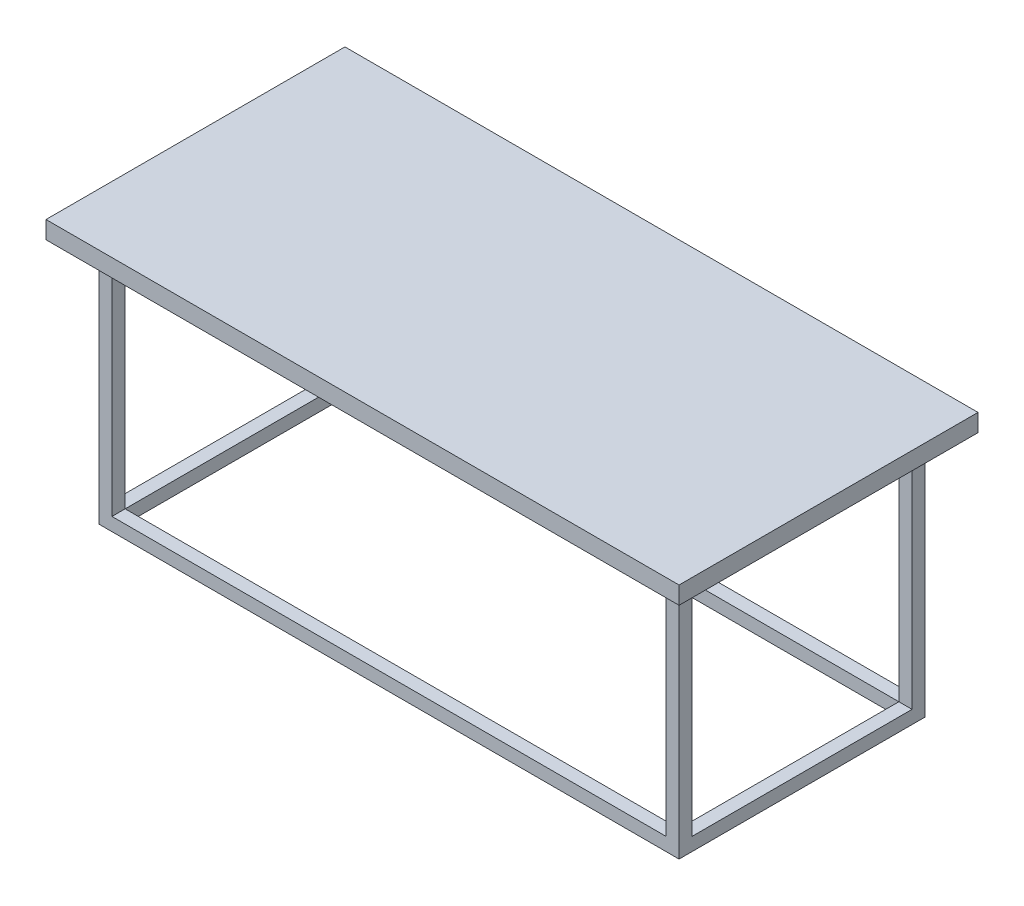
SolidWorks part; units mm, degrees
ref_plane "Front Plane" through (0, 0, 0) normal (0, 0, 1) x (1, 0, 0)
ref_plane "Top Plane" through (0, 0, 0) normal (0, 1, 0) x (1, 0, 0)
ref_plane "Right Plane" through (0, 0, 0) normal (1, 0, 0) x (0, 0, -1)
sketch "Sketch1" plane through (0, 0, 0) normal (0, 1, 0) x (1, 0, 0)
  line L1 (914.4, -431.8) -> (-914.4, -431.8)
  line L2 (914.4, -431.8) -> (914.4, 431.8)
  line L3 (914.4, 431.8) -> (-914.4, 431.8)
  line L4 (-914.4, -431.8) -> (-914.4, 431.8)
  line L5 (914.4, -431.8) -> (-914.4, 431.8) construction
  line L6 (914.4, 431.8) -> (-914.4, -431.8) construction
  point P0 (0, 0)
  dimension "D1" = 1828.8
  dimension "D2" = 863.6
extrude "Boss-Extrude1" add sketch "Sketch1" along normal blind 50.8
sketch "Sketch2" plane through (0, 0, 0) normal (0, -1, 0) x (1, 0, 0)
  line L0 (800.1, 317.5) -> (-800.1, 317.5)
  line L1 (838.2, -355.6) -> (-838.2, -355.6)
  line L2 (838.2, -355.6) -> (838.2, 355.6)
  line L3 (838.2, 355.6) -> (-838.2, 355.6)
  line L4 (-838.2, -355.6) -> (-838.2, 355.6)
  line L5 (838.2, -355.6) -> (-838.2, 355.6) construction
  line L6 (838.2, 355.6) -> (-838.2, -355.6) construction
  line L7 (-800.1, -317.5) -> (-800.1, 317.5)
  line L8 (800.1, -317.5) -> (-800.1, -317.5)
  line L9 (800.1, -317.5) -> (800.1, 317.5)
  point P0 (0, 0)
  dimension "D1" = 711.2
  dimension "D2" = 1676.4
  dimension "D3" = 38.1
extrude "Boss-Extrude2" add sketch "Sketch2" along normal blind 50.8
sketch "Sketch3" plane through (0, -50.8, 0) normal (0, -1, 0) x (1, 0, 0)
  line L1 (-838.2, 355.6) -> (-800.1, 355.6)
  line L2 (-838.2, 355.6) -> (-838.2, 317.5)
  line L3 (-838.2, 317.5) -> (-800.1, 317.5)
  line L4 (-800.1, 355.6) -> (-800.1, 317.5)
  line L5 (838.2, 355.6) -> (800.1, 355.6)
  line L6 (838.2, 355.6) -> (838.2, 317.5)
  line L7 (838.2, 317.5) -> (800.1, 317.5)
  line L8 (800.1, 355.6) -> (800.1, 317.5)
  line L9 (800.1, -317.5) -> (838.2, -317.5)
  line L10 (800.1, -317.5) -> (800.1, -355.6)
  line L11 (800.1, -355.6) -> (838.2, -355.6)
  line L12 (838.2, -317.5) -> (838.2, -355.6)
  line L13 (-838.2, -355.6) -> (-800.1, -355.6)
  line L14 (-838.2, -355.6) -> (-838.2, -317.5)
  line L15 (-838.2, -317.5) -> (-800.1, -317.5)
  line L16 (-800.1, -355.6) -> (-800.1, -317.5)
extrude "Boss-Extrude3" add sketch "Sketch3" along normal blind 660.4
sketch "Sketch4" plane through (-800.1, 0, 0) normal (1, 0, 0) x (0, 0, -1)
  line L0 (-317.5, -711.2) -> (-317.5, -50.8) construction
  line L1 (-355.6, -711.2) -> (-317.5, -711.2)
  line L2 (-355.6, -711.2) -> (-355.6, -673.1)
  line L3 (-355.6, -673.1) -> (-317.5, -673.1)
  line L4 (-317.5, -711.2) -> (-317.5, -673.1)
  line L5 (355.6, -711.2) -> (355.6, -50.8) construction
  line L6 (317.5, -711.2) -> (355.6, -711.2)
  line L7 (317.5, -711.2) -> (317.5, -673.1)
  line L8 (317.5, -673.1) -> (355.6, -673.1)
  line L9 (355.6, -711.2) -> (355.6, -673.1)
  dimension "D1" = 38.1
extrude "Boss-Extrude4" add sketch "Sketch4" along normal up to next
sketch "Sketch5" plane through (0, 0, -317.5) normal (0, 0, 1) x (1, 0, 0)
  line L1 (-838.2, -711.2) -> (-800.1, -711.2)
  line L2 (-838.2, -711.2) -> (-838.2, -673.1)
  line L3 (-838.2, -673.1) -> (-800.1, -673.1)
  line L4 (-800.1, -711.2) -> (-800.1, -673.1)
  line L5 (838.2, -711.2) -> (800.1, -711.2)
  line L6 (838.2, -711.2) -> (838.2, -673.1)
  line L7 (838.2, -673.1) -> (800.1, -673.1)
  line L8 (800.1, -711.2) -> (800.1, -673.1)
extrude "Boss-Extrude5" add sketch "Sketch5" along normal up to next
